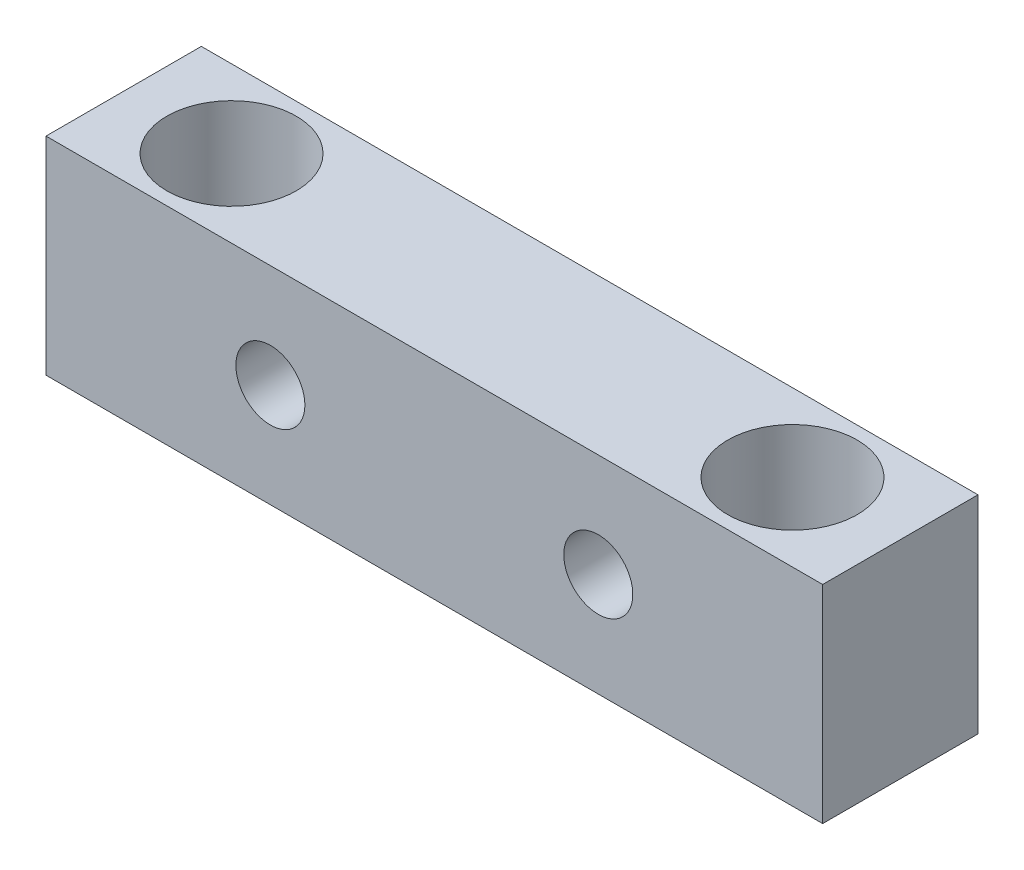
SolidWorks part; units mm, degrees
ref_plane "Front Plane" through (0, 0, 0) normal (0, 0, 1) x (1, 0, 0)
ref_plane "Top Plane" through (0, 0, 0) normal (0, 1, 0) x (1, 0, 0)
ref_plane "Right Plane" through (0, 0, 0) normal (1, 0, 0) x (0, 0, -1)
sketch "Sketch1" plane through (0, 0, 0) normal (0, 0, 1) x (1, 0, 0)
  line L0 (0, 0) -> (0, 14.0353) construction
  line L1 (-45, -12) -> (45, -12)
  line L2 (-45, -12) -> (-45, 12)
  line L3 (-45, 12) -> (45, 12)
  line L4 (45, -12) -> (45, 12)
  line L5 (-45, -12) -> (45, 12) construction
  line L6 (-45, 12) -> (45, -12) construction
  line L7 (0, 0) -> (-19, 0) construction
  circle A0 centre (-19, 0) radius 4
  circle A1 centre (19, 0) radius 4
  point P0 (0, 0)
  dimension "D1" = 8
  dimension "D4" = 38
  dimension "D2" = 24
  dimension "D3" = 90
extrude "Boss-Extrude1" add sketch "Sketch1" along normal mid plane 18
sketch "Sketch2" plane through (0, 12, 0) normal (0, 1, 0) x (1, 0, 0)
  line L0 (-45, 0) -> (45, 0) construction
  line L1 (-45, -9) -> (-45, 9) construction
  line L2 (45, -9) -> (45, 9) construction
  line L3 (0, 9) -> (0, -9) construction
  line L4 (45, 9) -> (-45, 9) construction
  line L5 (45, -9) -> (-45, -9) construction
  circle A0 centre (-32.5, 0) radius 7.5
  circle A1 centre (32.5, 0) radius 7.5
  dimension "D1" = 15
  dimension "D2" = 65
extrude "Cut-Extrude3" cut sketch "Sketch2" against normal through all
